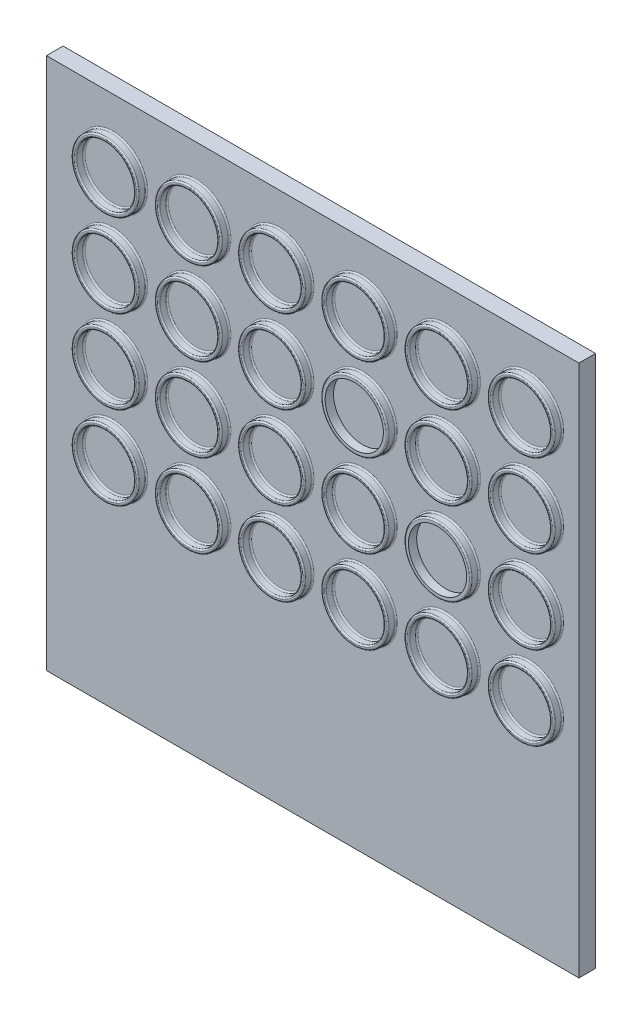
SolidWorks part; units mm, degrees
ref_plane "Front Plane" through (0, 0, 0) normal (0, 0, 1) x (1, 0, 0)
ref_plane "Top Plane" through (0, 0, 0) normal (0, 1, 0) x (1, 0, 0)
ref_plane "Right Plane" through (0, 0, 0) normal (1, 0, 0) x (0, 0, -1)
sketch "Sketch1" plane through (0, 0, 0) normal (0, 0, 1) x (1, 0, 0)
  line L1 (-101.6, -101.6) -> (101.6, -101.6)
  line L2 (-101.6, -101.6) -> (-101.6, 101.6)
  line L3 (-101.6, 101.6) -> (101.6, 101.6)
  line L4 (101.6, -101.6) -> (101.6, 101.6)
  line L5 (-101.6, -101.6) -> (101.6, 101.6) construction
  line L6 (-101.6, 101.6) -> (101.6, -101.6) construction
  point P0 (0, 0)
  dimension "D1" = 203.2
  dimension "D2" = 203.2
extrude "Boss-Extrude1" add sketch "Sketch1" along normal blind 6.35
sketch "Sketch2" plane through (0, 0, 6.35) normal (0, 0, 1) x (1, 0, 0)
  line L0 (101.6, 101.6) -> (-101.6, 101.6) construction
  line L1 (-101.6, 101.6) -> (-101.6, -101.6) construction
  circle A0 centre (-76.2, 76.2) radius 12.7
  circle A1 centre (-44.45, 76.2) radius 12.7
  circle A2 centre (-12.7, 76.2) radius 12.7
  circle A3 centre (19.05, 76.2) radius 12.7
  circle A4 centre (50.8, 76.2) radius 12.7
  circle A5 centre (82.55, 76.2) radius 12.7
  circle A6 centre (-44.45, 44.45) radius 12.7
  circle A7 centre (-12.7, 44.45) radius 12.7
  circle A8 centre (19.05, 44.45) radius 12.7
  circle A9 centre (50.8, 44.45) radius 12.7
  circle A10 centre (82.55, 44.45) radius 12.7
  circle A11 centre (-44.45, 44.45) radius 12.7
  circle A12 centre (-76.2, 44.45) radius 12.7
  circle A13 centre (-76.2, 12.7) radius 12.7
  circle A14 centre (-76.2, -19.05) radius 12.7
  circle A15 centre (-44.45, 12.7) radius 12.7
  circle A16 centre (-12.7, 44.45) radius 12.7
  circle A17 centre (-78.74, 76.2) radius 12.7 [skipped]
  circle A18 centre (-78.74, 44.45) radius 12.7 [skipped]
  circle A19 centre (-78.74, 12.7) radius 12.7 [skipped]
  circle A20 centre (-78.74, -19.05) radius 12.7 [skipped]
  circle A21 centre (-78.74, -50.8) radius 12.7 [skipped]
  circle A22 centre (-78.74, -82.55) radius 12.7 [skipped]
  circle A23 centre (-76.2, -50.8) radius 12.7 [skipped]
  circle A24 centre (-76.2, -82.55) radius 12.7 [skipped]
  circle A25 centre (-12.7, 12.7) radius 12.7
  circle A26 centre (19.05, 44.45) radius 12.7
  circle A27 centre (19.05, 12.7) radius 12.7
  circle A28 centre (50.8, 44.45) radius 12.7
  circle A29 centre (50.8, 12.7) radius 12.7
  circle A30 centre (82.55, 44.45) radius 12.7
  circle A31 centre (82.55, 12.7) radius 12.7
  circle A32 centre (-44.45, 44.45) radius 12.7
  circle A33 centre (-44.45, 12.7) radius 12.7
  circle A34 centre (-44.45, -19.05) radius 12.7
  circle A35 centre (-12.7, 44.45) radius 12.7
  circle A36 centre (-12.7, 12.7) radius 12.7
  circle A37 centre (-12.7, -19.05) radius 12.7
  circle A38 centre (19.05, 44.45) radius 12.7
  circle A39 centre (19.05, 12.7) radius 12.7
  circle A40 centre (19.05, -19.05) radius 12.7
  circle A41 centre (50.8, 44.45) radius 12.7
  circle A42 centre (50.8, 12.7) radius 12.7
  circle A43 centre (50.8, -19.05) radius 12.7
  circle A44 centre (82.55, 44.45) radius 12.7
  circle A45 centre (82.55, 12.7) radius 12.7
  circle A46 centre (82.55, -19.05) radius 12.7
  circle A47 centre (-76.2, 76.2) radius 11.1125
  circle A48 centre (-44.45, 76.2) radius 11.1125
  circle A49 centre (-12.7, 76.2) radius 11.1125
  circle A50 centre (19.05, 76.2) radius 11.1125
  circle A51 centre (50.8, 76.2) radius 11.1125
  circle A52 centre (82.55, 76.2) radius 11.1125
  circle A53 centre (-44.45, 44.45) radius 11.1125
  circle A54 centre (-12.7, 44.45) radius 11.1125
  circle A55 centre (19.05, 44.45) radius 11.1125
  circle A56 centre (50.8, 44.45) radius 11.1125
  circle A57 centre (-76.2, 44.45) radius 11.1125
  circle A58 centre (-76.2, 12.7) radius 11.1125
  circle A59 centre (-76.2, -19.05) radius 11.1125
  circle A60 centre (-73.66, 44.45) radius 11.1125 [skipped]
  circle A61 centre (-73.66, 76.2) radius 11.1125 [skipped]
  circle A62 centre (-73.66, 12.7) radius 11.1125 [skipped]
  circle A63 centre (-73.66, -19.05) radius 11.1125 [skipped]
  circle A64 centre (82.55, 44.45) radius 11.1125
  circle A65 centre (-44.45, 44.45) radius 11.1125
  circle A66 centre (-44.45, 12.7) radius 11.1125
  circle A67 centre (-44.45, -19.05) radius 11.1125
  circle A68 centre (-12.7, 44.45) radius 11.1125
  circle A69 centre (-12.7, 12.7) radius 11.1125
  circle A70 centre (-12.7, -19.05) radius 11.1125
  circle A71 centre (19.05, 44.45) radius 11.1125
  circle A72 centre (19.05, 12.7) radius 11.1125
  circle A73 centre (19.05, -19.05) radius 11.1125
  circle A74 centre (50.8, 44.45) radius 11.1125
  circle A75 centre (50.8, 12.7) radius 11.1125
  circle A76 centre (50.8, -19.05) radius 11.1125
  circle A77 centre (82.55, 44.45) radius 11.1125
  circle A78 centre (82.55, 12.7) radius 11.1125
  circle A79 centre (82.55, -19.05) radius 11.1125
  circle A80 centre (19.05, 44.45) radius 11.1125
  circle A81 centre (50.8, 12.7) radius 12.7
  dimension "D1" = 25.4
  dimension "D2" = 25.4
  dimension "D3" = 25.4
  dimension "D10" = 31.75
  dimension "D11" = 22.225
  dimension "D4" = 6
  dimension "D5" = 2
  dimension "D6" = 6
  dimension "D7" = 6
  dimension "D8" = 6
  dimension "D9" = 6
  dimension "D12" = 6
  dimension "D14" = 2
  dimension "D13" = 4
extrude "Boss-Extrude2" add sketch "Sketch2" along normal blind 3.175 contours A0 | A1 | A2 | A3 | A4 | A5 | A9 | A8 | A12 | A6 | A7 | A13 | A15 | A25 | A27 | A10 | A31 | A46 | A43 | A40 | A37 | A34 | A14 | A29
sketch "Sketch3" plane through (0, 0, 9.525) normal (0, 0, 1) x (1, 0, 0)
  circle A0 centre (19.05, 44.45) radius 11.1125
  circle A1 centre (50.8, 12.7) radius 11.1125
  dimension "D1" = 22.225
  dimension "D2" = 22.225
extrude "Cut-Extrude1" cut sketch "Sketch3" against normal blind 3.175
fillet "Fillet2" radius 0.5397 46 edges at (31.75, 44.45, 9.525) (-63.5, 44.45, 9.525) (-65.0875, 44.45, 9.525) (-31.75, 44.45, 9.525) (-33.3375, 44.45, 9.525) (0, 44.45, 9.525) (-1.5875, 44.45, 9.525) (-63.5, 12.7, 9.525) (-65.0875, 12.7, 9.525) (-31.75, 12.7, 9.525) (-33.3375, 12.7, 9.525) (0, 12.7, 9.525) (-1.5875, 12.7, 9.525) (31.75, 12.7, 9.525) (30.1625, 12.7, 9.525) (95.25, 44.45, 9.525) (93.6625, 44.45, 9.525) (95.25, 12.7, 9.525) (93.6625, 12.7, 9.525) (95.25, -19.05, 9.525) (93.6625, -19.05, 9.525) (63.5, -19.05, 9.525) (61.9125, -19.05, 9.525) (31.75, -19.05, 9.525) (30.1625, -19.05, 9.525) (0, -19.05, 9.525) (-1.5875, -19.05, 9.525) (-31.75, -19.05, 9.525) (-33.3375, -19.05, 9.525) (-63.5, -19.05, 9.525) (-65.0875, -19.05, 9.525) (63.5, 12.7, 9.525) (63.5, 44.45, 9.525) (61.9125, 44.45, 9.525) (95.25, 76.2, 9.525) (93.6625, 76.2, 9.525) (63.5, 76.2, 9.525) (61.9125, 76.2, 9.525) (31.75, 76.2, 9.525) (30.1625, 76.2, 9.525) (-1.5875, 76.2, 9.525) (-31.75, 76.2, 9.525) (-33.3375, 76.2, 9.525) (0, 76.2, 9.525) (-63.5, 76.2, 9.525) (-65.0875, 76.2, 9.525)
fillet "Fillet3" radius 0.5397 46 edges at (-65.0875, 44.45, 6.35) (-33.3375, 44.45, 6.35) (-1.5875, 44.45, 6.35) (-65.0875, 12.7, 6.35) (-33.3375, 12.7, 6.35) (-1.5875, 12.7, 6.35) (30.1625, 12.7, 6.35) (93.6625, 44.45, 6.35) (93.6625, 12.7, 6.35) (93.6625, -19.05, 6.35) (61.9125, -19.05, 6.35) (30.1625, -19.05, 6.35) (-1.5875, -19.05, 6.35) (-33.3375, -19.05, 6.35) (-65.0875, -19.05, 6.35) (61.9125, 44.45, 6.35) (93.6625, 76.2, 6.35) (61.9125, 76.2, 6.35) (30.1625, 76.2, 6.35) (-1.5875, 76.2, 6.35) (-33.3375, 76.2, 6.35) (-65.0875, 76.2, 6.35) (-57.15, 76.2, 6.35) (-25.4, 76.2, 6.35) (6.35, 76.2, 6.35) (38.1, 76.2, 6.35) (69.85, 76.2, 6.35) (38.1, 44.45, 6.35) (38.1, 12.7, 6.35) (-88.9, -19.05, 6.35) (-57.15, -19.05, 6.35) (-25.4, -19.05, 6.35) (6.35, -19.05, 6.35) (38.1, -19.05, 6.35) (69.85, -19.05, 6.35) (69.85, 12.7, 6.35) (69.85, 44.45, 6.35) (6.35, 12.7, 6.35) (-25.4, 12.7, 6.35) (-57.15, 12.7, 6.35) (-88.9, 12.7, 6.35) (-25.4, 44.45, 6.35) (-57.15, 44.45, 6.35) (-88.9, 44.45, 6.35) (6.35, 44.45, 6.35) (-88.9, 76.2, 6.35)
